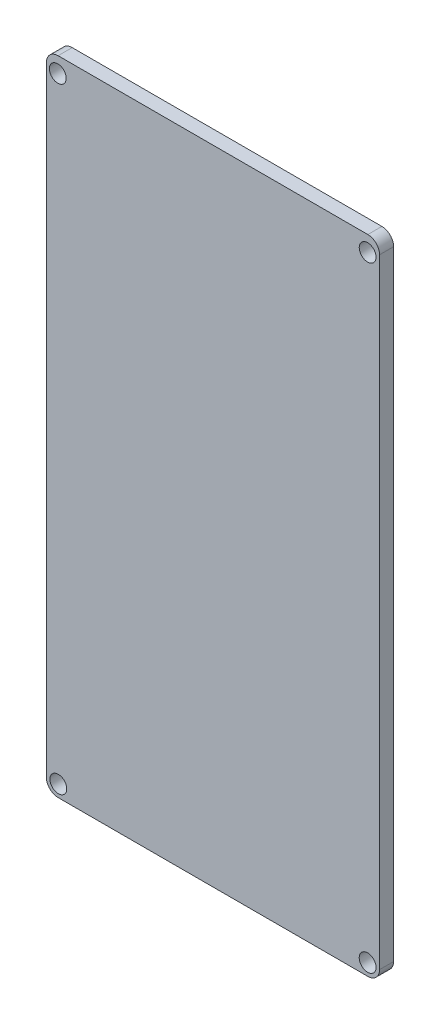
SolidWorks part; units mm, degrees
material "Plastique personnalisé"
ref_plane "Plan de face" through (0, 0, 0) normal (0, 0, 1) x (1, 0, 0)
ref_plane "Plan de dessus" through (0, 0, 0) normal (0, 1, 0) x (1, 0, 0)
ref_plane "Plan de droite" through (0, 0, 0) normal (1, 0, 0) x (0, 0, -1)
sketch "Model" plane through (0, 0, 0) normal (0, 0, 1) x (1, 0, 0)
  line L1601 (83.185, -89.2238) -> (62.865, -89.2238)
  line L1602 (84.455, -93.0338) -> (84.455, -90.4938)
  line L1603 (104.775, -93.0338) -> (84.455, -93.0338)
  line L1604 (104.775, -90.4938) -> (104.775, -93.0338)
  line L1605 (128.905, -89.2238) -> (106.045, -89.2238)
  line L1606 (60.325, -93.0338) -> (60.325, -91.7638)
  line L1607 (131.445, -93.0338) -> (131.445, -91.7638)
  line L1608 (60.325, -195.9038) -> (60.325, -93.0338)
  line L1609 (131.445, -223.8438) -> (131.445, -221.3038)
  line L1610 (128.905, -226.3838) -> (126.365, -226.3838)
  line L1611 (62.865, -226.3838) -> (65.405, -226.3838)
  line L1612 (60.325, -223.8438) -> (60.325, -221.3038)
  line L1613 (131.445, -221.3038) -> (131.445, -208.6038)
  line L1614 (65.405, -226.3838) -> (126.365, -226.3838)
  line L1615 (60.325, -195.9038) -> (60.325, -221.3038)
  line L1616 (131.445, -195.9038) -> (131.445, -208.6038)
  line L1617 (131.445, -93.0338) -> (131.445, -195.9038)
  spline S0 degree 3 poles (62.865, -89.2238) (62.1913, -89.2238) (61.5453, -89.4914) (61.0689, -89.9677) knots 0 0 0 0 1 1 1 1
  spline S1 degree 3 poles (61.0689, -89.9677) (60.5926, -90.4441) (60.325, -91.0901) (60.325, -91.7638) knots 0 0 0 0 1 1 1 1
  spline S2 degree 3 poles (106.045, -89.2238) (105.7082, -89.2238) (105.3851, -89.3576) (105.147, -89.5958) knots 0 0 0 0 1 1 1 1
  spline S3 degree 3 poles (105.147, -89.5958) (104.9088, -89.8339) (104.775, -90.157) (104.775, -90.4938) knots 0 0 0 0 1 1 1 1
  spline S4 degree 3 poles (131.445, -91.7638) (131.445, -91.0901) (131.1774, -90.4441) (130.7011, -89.9677) knots 0 0 0 0 1 1 1 1
  spline S5 degree 3 poles (130.7011, -89.9677) (130.2247, -89.4914) (129.5787, -89.2238) (128.905, -89.2238) knots 0 0 0 0 1 1 1 1
  spline S6 degree 3 poles (84.455, -90.4938) (84.455, -90.157) (84.3212, -89.8339) (84.083, -89.5958) knots 0 0 0 0 1 1 1 1
  spline S7 degree 3 poles (84.083, -89.5958) (83.8449, -89.3576) (83.5218, -89.2238) (83.185, -89.2238) knots 0 0 0 0 1 1 1 1
  spline S8 degree 3 poles (60.325, -223.8438) (60.325, -224.5174) (60.5926, -225.1635) (61.0689, -225.6398) knots 0 0 0 0 1 1 1 1
  spline S9 degree 3 poles (61.0689, -225.6398) (61.5453, -226.1162) (62.1913, -226.3838) (62.865, -226.3838) knots 0 0 0 0 1 1 1 1
  spline S10 degree 3 poles (128.905, -226.3838) (129.5787, -226.3838) (130.2247, -226.1162) (130.7011, -225.6398) knots 0 0 0 0 1 1 1 1
  spline S11 degree 3 poles (130.7011, -225.6398) (131.1774, -225.1635) (131.445, -224.5174) (131.445, -223.8438) knots 0 0 0 0 1 1 1 1
  spline S12 degree 3 poles (130.7011, -223.8438) (130.7011, -224.4854) (130.3587, -225.0784) (129.803, -225.3992) knots 0 0 0 0 1 1 1 1
  spline S13 degree 3 poles (129.803, -225.3992) (129.2473, -225.72) (128.5627, -225.72) (128.007, -225.3992) knots 0 0 0 0 1 1 1 1
  spline S14 degree 3 poles (128.007, -225.3992) (127.4513, -225.0784) (127.1089, -224.4854) (127.1089, -223.8438) knots 0 0 0 0 1 1 1 1
  spline S15 degree 3 poles (127.1089, -223.8438) (127.1089, -223.2021) (127.4513, -222.6092) (128.007, -222.2884) knots 0 0 0 0 1 1 1 1
  spline S16 degree 3 poles (128.007, -222.2884) (128.5627, -221.9675) (129.2473, -221.9675) (129.803, -222.2884) knots 0 0 0 0 1 1 1 1
  spline S17 degree 3 poles (129.803, -222.2884) (130.3587, -222.6092) (130.7011, -223.2021) (130.7011, -223.8438) knots 0 0 0 0 1 1 1 1
  spline S18 degree 3 poles (130.7011, -92.5438) (130.7011, -93.1855) (130.3587, -93.7784) (129.803, -94.0992) knots 0 0 0 0 1 1 1 1
  spline S19 degree 3 poles (129.803, -94.0992) (129.2473, -94.4201) (128.5627, -94.4201) (128.007, -94.0992) knots 0 0 0 0 1 1 1 1
  spline S20 degree 3 poles (128.007, -94.0992) (127.4513, -93.7784) (127.1089, -93.1855) (127.1089, -92.5438) knots 0 0 0 0 1 1 1 1
  spline S21 degree 3 poles (127.1089, -92.5438) (127.1089, -91.9021) (127.4513, -91.3092) (128.007, -90.9884) knots 0 0 0 0 1 1 1 1
  spline S22 degree 3 poles (128.007, -90.9884) (128.5627, -90.6676) (129.2473, -90.6676) (129.803, -90.9884) knots 0 0 0 0 1 1 1 1
  spline S23 degree 3 poles (129.803, -90.9884) (130.3587, -91.3092) (130.7011, -91.9021) (130.7011, -92.5438) knots 0 0 0 0 1 1 1 1
  spline S24 degree 3 poles (64.5521, -92.5438) (64.5521, -93.1855) (64.2098, -93.7784) (63.6541, -94.0992) knots 0 0 0 0 1 1 1 1
  spline S25 degree 3 poles (63.6541, -94.0992) (63.0984, -94.4201) (62.4137, -94.4201) (61.858, -94.0992) knots 0 0 0 0 1 1 1 1
  spline S26 degree 3 poles (61.858, -94.0992) (61.3023, -93.7784) (60.96, -93.1855) (60.96, -92.5438) knots 0 0 0 0 1 1 1 1
  spline S27 degree 3 poles (60.96, -92.5438) (60.96, -91.9021) (61.3023, -91.3092) (61.858, -90.9884) knots 0 0 0 0 1 1 1 1
  spline S28 degree 3 poles (61.858, -90.9884) (62.4137, -90.6676) (63.0984, -90.6676) (63.6541, -90.9884) knots 0 0 0 0 1 1 1 1
  spline S29 degree 3 poles (63.6541, -90.9884) (64.2098, -91.3092) (64.5521, -91.9021) (64.5521, -92.5438) knots 0 0 0 0 1 1 1 1
  spline S30 degree 3 poles (64.6611, -223.8438) (64.6611, -224.4854) (64.3187, -225.0784) (63.763, -225.3992) knots 0 0 0 0 1 1 1 1
  spline S31 degree 3 poles (63.763, -225.3992) (63.2073, -225.72) (62.5227, -225.72) (61.967, -225.3992) knots 0 0 0 0 1 1 1 1
  spline S32 degree 3 poles (61.967, -225.3992) (61.4113, -225.0784) (61.0689, -224.4854) (61.0689, -223.8438) knots 0 0 0 0 1 1 1 1
  spline S33 degree 3 poles (61.0689, -223.8438) (61.0689, -223.2021) (61.4113, -222.6092) (61.967, -222.2884) knots 0 0 0 0 1 1 1 1
  spline S34 degree 3 poles (61.967, -222.2884) (62.5227, -221.9675) (63.2073, -221.9675) (63.763, -222.2884) knots 0 0 0 0 1 1 1 1
  spline S35 degree 3 poles (63.763, -222.2884) (64.3187, -222.6092) (64.6611, -223.2021) (64.6611, -223.8438) knots 0 0 0 0 1 1 1 1
sketch "Esquisse2" plane through (0, 0, 0) normal (0, 0, 1) x (1, 0, 0)
  line L0 (62.865, -89.2238) -> (139.1173, -89.2238) construction
  line L1 (131.445, -144.4688) -> (131.445, -87.2561) construction
  line L2 (131.445, -93.0338) -> (131.445, -195.9038) construction
  line L3 (60.325, -208.6038) -> (60.325, -230.3143) construction
  line L4 (60.325, -195.9038) -> (60.325, -221.3038) construction
  line L5 (76.6644, -226.3838) -> (53.6251, -226.3838) construction
  line L6 (65.405, -226.3838) -> (126.365, -226.3838) construction
  line L8 (62.825, -226.3838) -> (128.945, -226.3838)
  line L9 (60.325, -223.8838) -> (60.325, -91.7238)
  line L10 (62.825, -89.2238) -> (128.945, -89.2238)
  line L11 (131.445, -223.8838) -> (131.445, -91.7238)
  circle A0 centre (128.905, -223.8438) radius 1.7961
  circle A1 centre (62.8728, -223.8483) radius 1.7961
  circle A2 centre (62.756, -92.5438) radius 1.7961
  circle A3 centre (128.905, -92.5438) radius 1.7961
  arc A4 (128.945, -226.3838) -> (131.445, -223.8838) centre (128.945, -223.8838) ccw
  arc A5 (62.825, -226.3838) -> (60.325, -223.8838) centre (62.825, -223.8838) cw
  arc A6 (60.325, -91.7238) -> (62.825, -89.2238) centre (62.825, -91.7238) cw
  arc A7 (128.945, -89.2238) -> (131.445, -91.7238) centre (128.945, -91.7238) cw
  point P42 (60.325, -226.3838)
  point P47 (131.445, -89.2238)
  dimension "D1" = 2.5
extrude "Boss.-Extru.1" add sketch "Esquisse2" against normal blind 3
